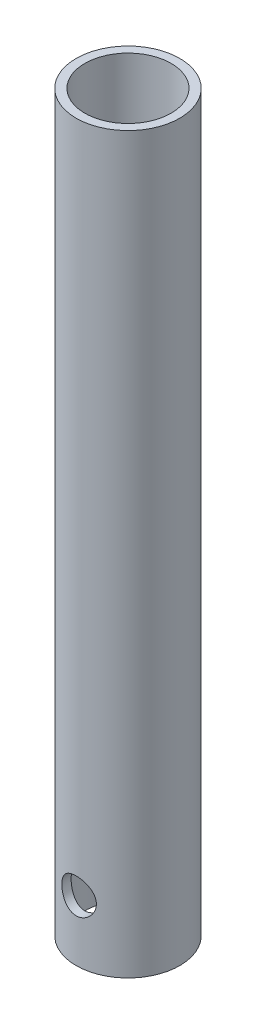
SolidWorks part; units mm, degrees
material "Thornel Mat VMA"
ref_plane "前视基准面" through (0, 0, 0) normal (0, 0, 1) x (1, 0, 0)
ref_plane "上视基准面" through (0, 0, 0) normal (0, 1, 0) x (1, 0, 0)
ref_plane "右视基准面" through (0, 0, 0) normal (1, 0, 0) x (0, 0, -1)
sketch "草图1" plane through (0, 0, 0) normal (0, 1, 0) x (1, 0, 0)
  circle A1 centre (0, 0) radius 6
  dimension "D1" = 12
extrude "拉伸-薄壁1" add sketch "草图1" along normal blind 85 thin thin type one direction reverse wall 1
sketch "草图2" plane through (0, 0, 0) normal (0, 0, 1) x (1, 0, 0)
  line L0 (-6, 0) -> (6, 0) construction
  circle A0 centre (0, 7) radius 2
  dimension "D1" = 4
  dimension "D2" = 7
extrude "切除-拉伸1" cut sketch "草图2" against normal through all both and the other way through all
